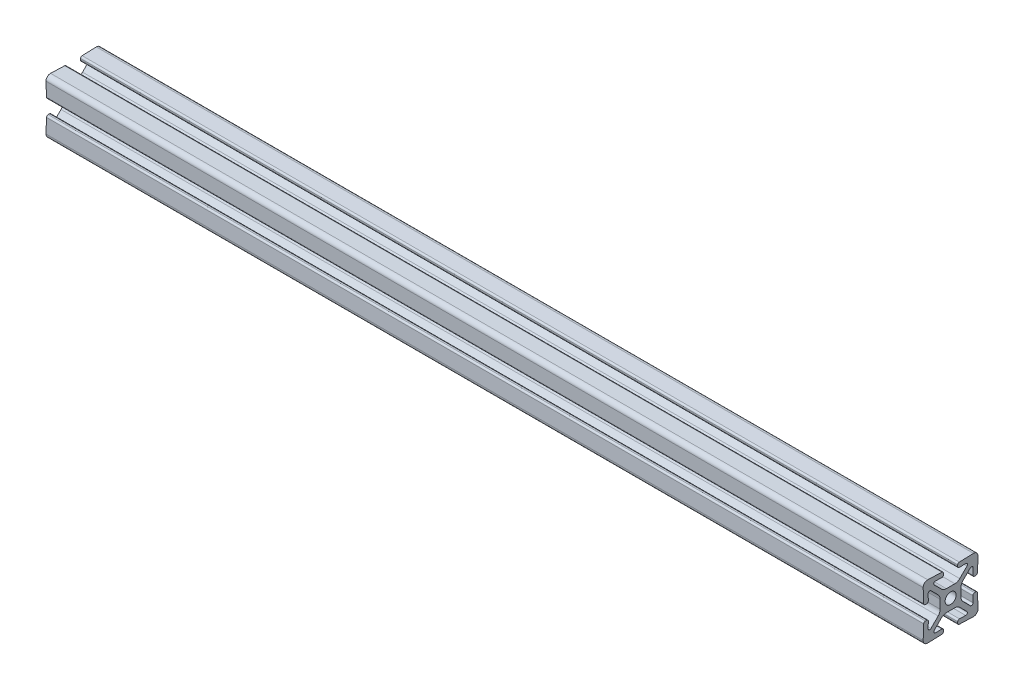
SolidWorks part; units mm, degrees
ref_plane "Front Plane" through (0, 0, 0) normal (0, 0, 1) x (1, 0, 0)
ref_plane "Top Plane" through (0, 0, 0) normal (0, 1, 0) x (1, 0, 0)
ref_plane "Right Plane" through (0, 0, 0) normal (1, 0, 0) x (0, 0, -1)
sketch "Sketch1" plane through (0, 0, 0) normal (1, 0, 0) x (0, 0, -1)
  line L0 (0, -12.7) -> (0, 12.7) construction
  line L1 (-7.874, 12.7) -> (7.874, 12.7) construction
  line L2 (-12.7, 0) -> (12.7, 0) construction
  line L3 (-7.874, 12.7) -> (-7.874, 4.826) construction
  line L4 (-3.302, 12.7) -> (3.302, 12.7) construction
  line L5 (-12.7, -12.7) -> (12.7, -12.7) construction
  line L6 (-12.7, 12.7) -> (12.7, 12.7) construction
  circle A0 centre (0, 0) radius 2.54 construction
  point P7 (0, 12.7)
  point P10 (0, 0)
  point P13 (0, 0)
  point P16 (0, 12.7)
  point P17 (-3.302, 12.7)
  point P18 (3.302, 12.7)
  point P21 (0, -12.7)
  point P24 (0, 12.7)
  dimension "Center Hole Diameter" = 5.08
  dimension "Rail Width" = 25.4
  dimension "Rail Height" = 25.4
  dimension "T-Slot Depth" = 7.874
  dimension "D1" = 15.748
  dimension "T-Slot Width" = 6.604
  dimension "D2" = 12.7
sketch "Sketch2" plane through (0, 0, 0) normal (0, 0, 1) x (1, 0, 0)
  line L0 (-203.2, 0) -> (203.2, 0) construction
  line L1 (0, 0) -> (0, 26.104) construction
  line L2 (203.2, -12.7) -> (203.2, 12.7) construction
  line L3 (-203.2, -12.7) -> (-203.2, 12.7) construction
  point P3 (-165.1, 0)
  point P8 (0, 0)
  point P9 (165.1, 0)
  point P12 (203.2, 0)
  point P15 (-203.2, 0)
  dimension "Length" = 406.4
  dimension "D1" = 38.1
  dimension "D2" = 25.4
sketch "Sketch3" plane through (0, 0, 0) normal (1, 0, 0) x (0, 0, -1)
  line L0 (0, 4.826) -> (1.9842, 4.826)
  line L1 (0, -12.7) -> (0, 12.7) construction
  line L2 (4.2293, 5.7559) -> (7.5866, 9.1132)
  line L6 (7.0212, 10.4136) -> (4.0906, 10.3112)
  line L7 (3.302, 11.0728) -> (3.302, 11.7082)
  line L8 (-7.874, 12.7) -> (7.874, 12.7) construction
  line L10 (0, 0) -> (12.7, 12.7) construction
  line L13 (0, 4.826) -> (0, 2.54)
  line L14 (4.826, 0) -> (2.54, 0)
  line L31 (4.826, 0) -> (4.826, 1.9842)
  line L32 (4.0374, 12.4697) -> (10.5971, 12.6988)
  line L33 (-12.7, 0) -> (12.7, 0) construction
  line L34 (-12.7, 12.7) -> (12.7, 12.7) construction
  line L35 (5.7559, 4.2293) -> (9.1132, 7.5866)
  line L36 (0, 12.7) -> (12.7, 12.7) construction
  line L37 (12.7, 12.7) -> (12.7, 8.0234) construction
  line L38 (11.0728, 3.302) -> (11.7082, 3.302)
  line L39 (10.4136, 7.0212) -> (10.3112, 4.0906)
  line L40 (12.6988, 10.5971) -> (12.4697, 4.0374)
  arc A0 (2.54, 0) -> (0, 2.54) centre (0, 0) ccw
  arc A1 (1.9842, 4.826) -> (4.2293, 5.7559) centre (1.9842, 8.001) ccw
  circle A2 centre (0, 0) radius 2.54 construction
  arc A7 (3.302, 11.7082) -> (4.0374, 12.4697) centre (4.064, 11.7082) cw
  arc A8 (4.0906, 10.3112) -> (3.302, 11.0728) centre (4.064, 11.0728) cw
  arc A14 (4.826, 1.9842) -> (5.7559, 4.2293) centre (8.001, 1.9842) cw
  arc A16 (10.5971, 12.6988) -> (12.6988, 10.5971) centre (10.668, 10.668) cw
  arc A17 (7.0212, 10.4136) -> (7.5866, 9.1132) centre (7.0478, 9.652) cw
  arc A18 (10.4136, 7.0212) -> (9.1132, 7.5866) centre (9.652, 7.0478) ccw
  arc A19 (10.3112, 4.0906) -> (11.0728, 3.302) centre (11.0728, 4.064) ccw
  arc A20 (11.7082, 3.302) -> (12.4697, 4.0374) centre (11.7082, 4.064) ccw
  point P37 (3.2994, 4.826)
  point P49 (12.7, 3.302)
  point P52 (3.302, 12.7)
  point P55 (3.302, 10.2837)
  dimension "D4" = 3.175
  dimension "D9" = 2.159
  dimension "D12" = 0.762
  dimension "D3" = 2.032
  dimension "D8" = 0.762
  dimension "D2" = 45
  dimension "D5" = 2
  dimension "D6" = 45
  dimension "D7" = 2.159
extrude "Boss-Extrude1" add sketch "Sketch3" against normal up to vertex (203.2 mm away) and the other way up to vertex (203.2 mm away) up to point (-203.2, 0, 0) other way up to point (203.2, 0, 0)
mirror "Mirror1" about plane through (0, 0, 0) normal (0, 1, 0) of bodies 104
mirror "Mirror2" about plane through (0, 0, 0) normal (0, 0, 1) of bodies 105
equation "\"D1@Sketch2\"=\"Rail Height@Sketch1\"*1.5"
equation "\"D2@Sketch2\"=\"Rail Height@Sketch1\""
